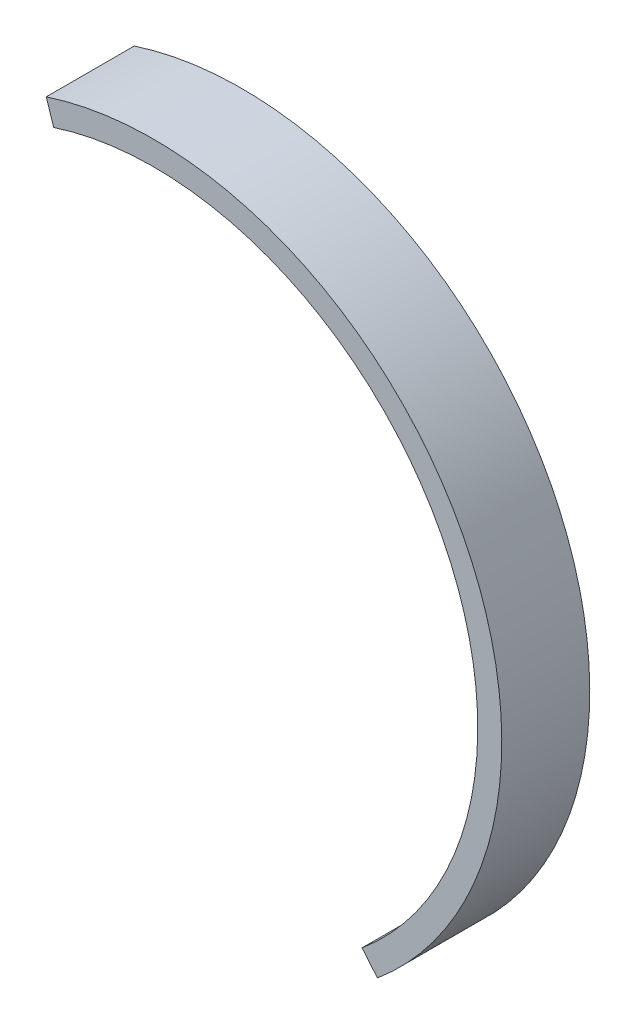
SolidWorks part; units mm, degrees
ref_plane "Plan1" through (0, 0, 0) normal (0, 0, 1) x (1, 0, 0)
ref_plane "Plan2" through (0, 0, 0) normal (0, 1, 0) x (1, 0, 0)
ref_plane "Plan3" through (0, 0, 0) normal (1, 0, 0) x (0, 0, -1)
sketch "Esquisse1" plane through (0, 0, 0) normal (0, 0, 1) x (1, 0, 0)
  line L0 (0, 0) -> (0, 103.8) construction
  line L1 (0, 0) -> (93.8, 0) construction
  line L2 (-25.0304, 77.0356) -> (-26.8845, 82.7419)
  line L3 (52.0658, -62.0496) -> (55.9225, -66.6459)
  arc A0 (55.9225, -66.6459) -> (-26.8845, 82.7419) centre (0, 0) ccw
  arc A1 (52.0658, -62.0496) -> (-25.0304, 77.0356) centre (0, 0) ccw
  dimension "D1" = 87
  dimension "D2" = 81
  dimension "D3" = 18
  dimension "D4" = 50
extrude "Base-Extrusion" add sketch "Esquisse1" along normal blind 22
